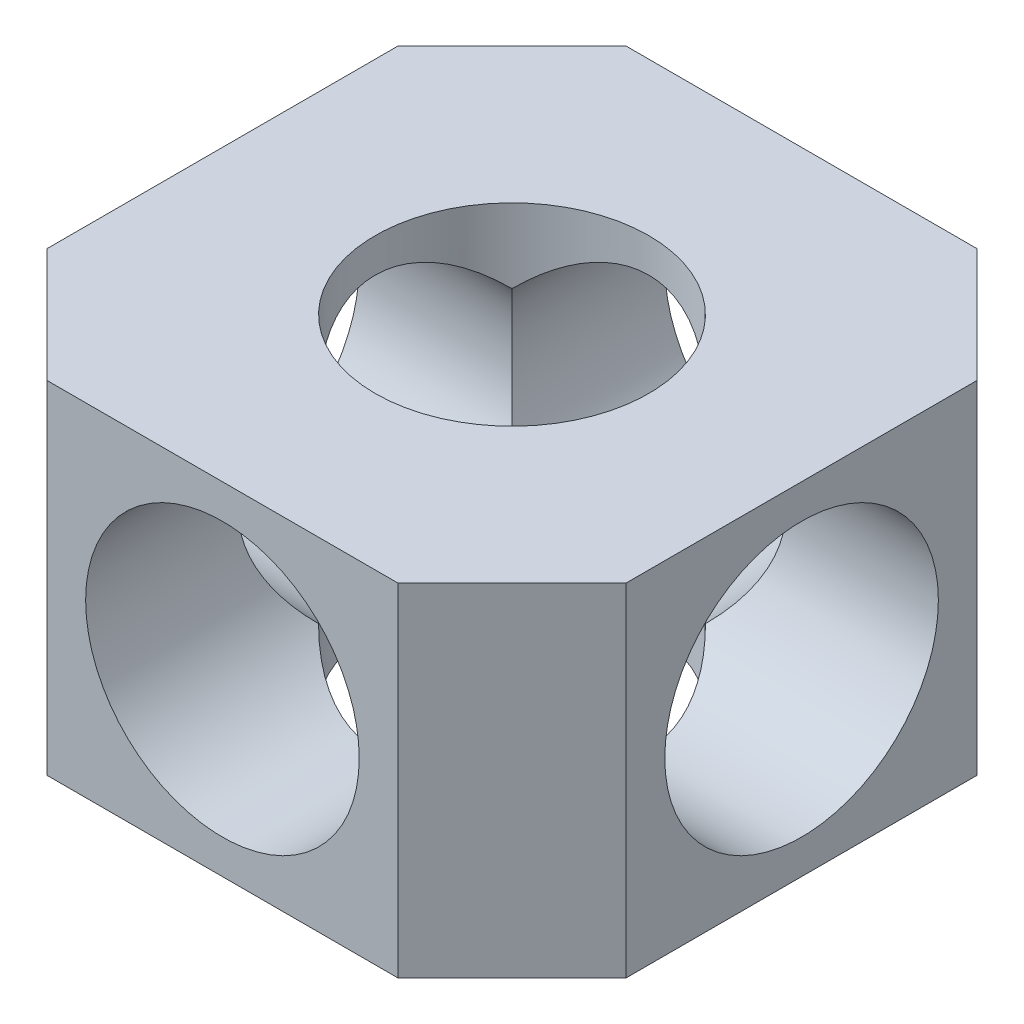
SolidWorks part; units mm, degrees
ref_plane "Front Plane" through (0, 0, 0) normal (0, 0, 1) x (1, 0, 0)
ref_plane "Top Plane" through (0, 0, 0) normal (0, 1, 0) x (1, 0, 0)
ref_plane "Right Plane" through (0, 0, 0) normal (1, 0, 0) x (0, 0, -1)
sketch "Sketch1" plane through (0, 0, 0) normal (0, 1, 0) x (1, 0, 0)
  line L1 (12.7, 12.7) -> (-12.7, 12.7)
  line L2 (12.7, 12.7) -> (12.7, -12.7)
  line L3 (12.7, -12.7) -> (-12.7, -12.7)
  line L4 (-12.7, 12.7) -> (-12.7, -12.7)
  line L5 (12.7, 12.7) -> (-12.7, -12.7) construction
  line L6 (12.7, -12.7) -> (-12.7, 12.7) construction
  point P0 (0, 0)
  dimension "D1" = 25.4
  dimension "D2" = 25.4
extrude "Boss-Extrude1" add sketch "Sketch1" along normal mid plane 15
hole_wizard "Hole1" positions "Sketch2" profile "Sketch3" legacy end condition through all
sketch "Sketch2" plane through (0, 7.5, 0) normal (0, 1, 0) x (1, 0, 0)
  point P0 (0, 0)
sketch "Sketch3" plane through (0, 7.5, 0) normal (1, 0, 0) x (0, 0, 1)
  line L0 (0, 0) -> (0, 15)
  line L1 (0, 15) -> (6, 15)
  line L2 (6, 15) -> (6, 0)
  line L3 (6, 0) -> (0, 0)
  line L4 (0, 110) -> (0, -10) construction
  dimension "Diameter" = 12
  dimension "Depth" = 15
hole_wizard "Hole2" positions "Sketch4" profile "Sketch5" legacy end condition through all
sketch "Sketch4" plane through (0, 0, 12.7) normal (0, 0, 1) x (1, 0, 0)
  point P0 (0, 0)
sketch "Sketch5" plane through (0, 0, 12.7) normal (1, 0, 0) x (0, -1, 0)
  line L0 (0, 0) -> (0, 25.4)
  line L1 (0, 25.4) -> (6, 25.4)
  line L2 (6, 25.4) -> (6, 0)
  line L3 (6, 0) -> (0, 0)
  line L4 (0, 110) -> (0, -10) construction
  dimension "Diameter" = 12
  dimension "Depth" = 25.4
hole_wizard "Hole3" positions "Sketch6" profile "Sketch7" legacy end condition through all
sketch "Sketch6" plane through (12.7, 0, 0) normal (1, 0, 0) x (0, 0, -1)
  point P0 (0, 0)
sketch "Sketch7" plane through (12.7, 0, 0) normal (0, 1, 0) x (0, 0, -1)
  line L0 (0, 0) -> (0, 25.4)
  line L1 (0, 25.4) -> (6, 25.4)
  line L2 (6, 25.4) -> (6, 0)
  line L3 (6, 0) -> (0, 0)
  line L4 (0, 110) -> (0, -10) construction
  dimension "Diameter" = 12
  dimension "Depth" = 25.4
chamfer "Chamfer1" distance 5 angle 45 4 edges at (-12.7, 0, -12.7) (-12.7, 0, 12.7) (12.7, 0, -12.7) (12.7, 0, 12.7)
